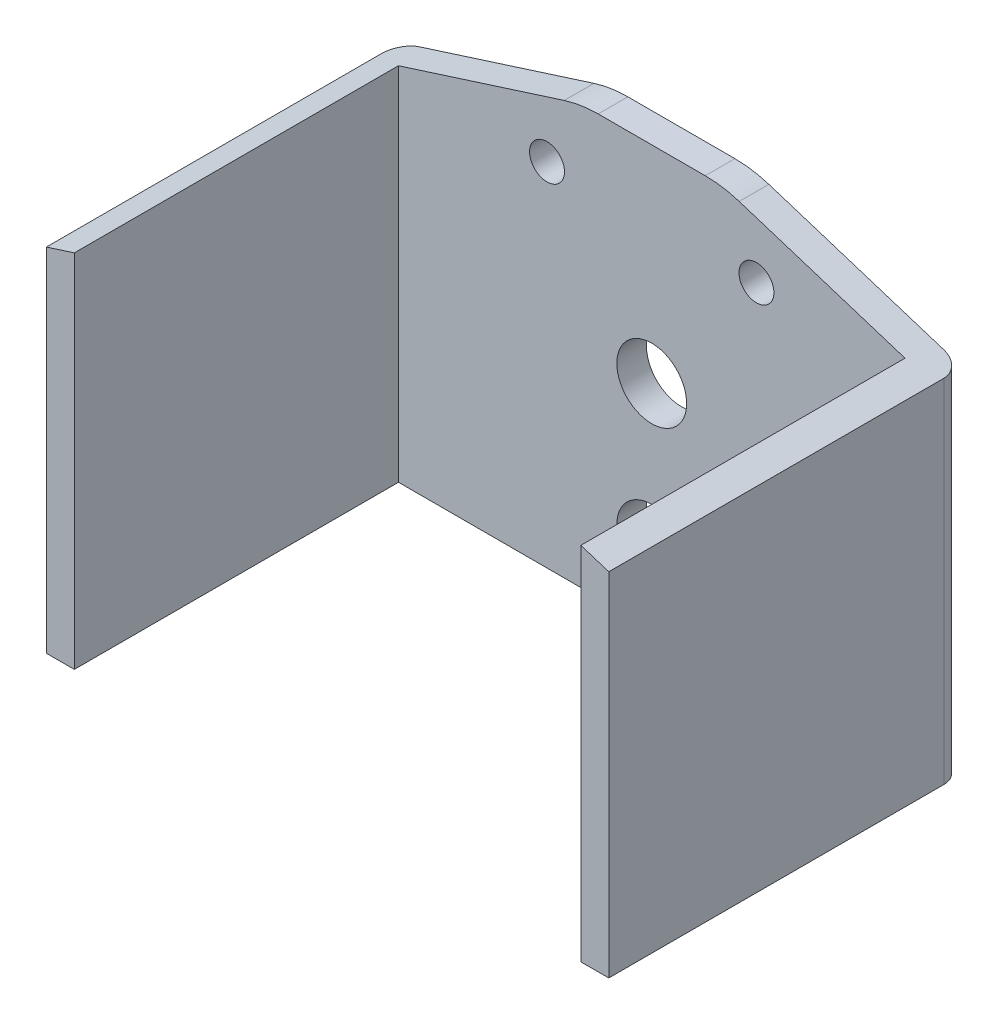
SolidWorks part; units mm, degrees
material "AISI 316 Stainless Steel Sheet (SS)"
ref_plane "Front Plane" through (0, 0, 0) normal (0, 0, 1) x (1, 0, 0)
ref_plane "Top Plane" through (0, 0, 0) normal (0, 1, 0) x (1, 0, 0)
ref_plane "Right Plane" through (0, 0, 0) normal (1, 0, 0) x (0, 0, -1)
sketch "Sketch8" plane through (0, 0, 0) normal (0, 1, 0) x (1, 0, 0)
  line L0 (-11.938, 0) -> (11.938, 0)
  line L1 (-12.7887, -0.8507) -> (-12.7887, -16.0907)
  line L2 (12.7887, -0.8507) -> (12.7887, -16.0907)
  line L8 (-12.7887, -16.0907) -> (-11.5187, -16.0907)
  line L9 (-11.5187, -16.0907) -> (-11.5187, -1.3481)
  line L10 (-11.5187, -1.3481) -> (11.5187, -1.3481)
  line L11 (11.5187, -1.3481) -> (11.5187, -16.0907)
  line L12 (11.5187, -16.0907) -> (12.7887, -16.0907)
  arc A0 (-11.938, 0) -> (-12.7887, -0.8507) centre (-11.938, -0.8507) ccw
  arc A1 (11.938, 0) -> (12.7887, -0.8507) centre (11.938, -0.8507) cw
  dimension "D4" = 1.27
  dimension "D1" = 1.27
  dimension "D2" = 15.24
  dimension "D3" = 15.24
  dimension "D5" = 23.876
  dimension "D6" = 1.3481
extrude "Boss-Extrude1" add sketch "Sketch8" along normal blind 19.05 contours L10 L11 L12 L2 A1 L0 A0 L1 L8 L9
sketch "Sketch9" plane through (0, 0, 0) normal (0, 0, -1) x (-1, 0, 0)
  line L0 (0, 19.05) -> (0, -19.05) construction
  line L1 (11.938, 19.05) -> (-11.938, 19.05) construction
  line L2 (-11.938, 16.002) -> (11.938, 16.002) construction
  line L3 (-11.938, 19.05) -> (-11.938, 0) construction
  line L4 (11.938, 19.05) -> (11.938, 0) construction
  line L5 (-12.7887, 16.002) -> (-3.2246, 19.05)
  line L6 (-12.7887, 19.05) -> (-12.7887, 0) construction
  line L8 (12.7887, 16.002) -> (3.2246, 19.05)
  line L9 (-12.7887, 16.002) -> (-12.7887, 19.05)
  line L10 (-12.7887, 19.05) -> (-3.2246, 19.05)
  line L11 (3.2246, 19.05) -> (12.7887, 19.05)
  line L12 (12.7887, 19.05) -> (12.7887, 16.002)
  line L13 (-12.7887, 9.652) -> (12.7887, 9.652) construction
  line L14 (12.7887, 19.05) -> (12.7887, 0) construction
  line L16 (11.938, 0) -> (-11.938, 0) construction
  circle A0 centre (0, 9.652) radius 1.5875
  circle A1 centre (0, 8.0645) radius 1.5875 [skipped]
  circle A3 centre (0, 3.302) radius 1.5875
  circle A6 centre (-4.7625, 16.002) radius 0.7938
  circle A7 centre (4.7625, 16.002) radius 0.7937
  dimension "D4" = 3.175
  dimension "D7" = 1.5875
  dimension "D8" = 1.5875
  dimension "D11" = 3.302
  dimension "D1" = 3.048
  dimension "D2" = 8.7134
  dimension "D3" = 6.35
  dimension "D6" = 2
  dimension "D9" = 4.7625
  dimension "D10" = 4.7625
  dimension "D5" = 2
extrude "Cut-Extrude3" cut sketch "Sketch9" against normal through all
fillet "Fillet1" radius 5.08 2 edges at (3.2246, 19.05, 0.6741) (-3.2246, 19.05, 0.6741)
